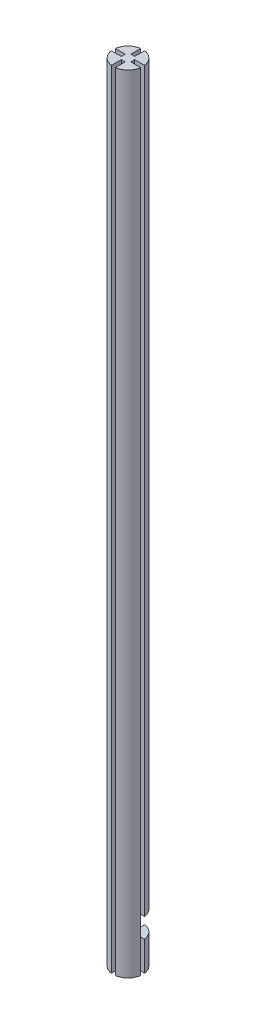
SolidWorks part; units mm, degrees
ref_plane "Front Plane" through (0, 0, 0) normal (0, 0, 1) x (1, 0, 0)
ref_plane "Top Plane" through (0, 0, 0) normal (0, 1, 0) x (1, 0, 0)
ref_plane "Right Plane" through (0, 0, 0) normal (1, 0, 0) x (0, 0, -1)
sketch "Sketch1" plane through (0, 0, 0) normal (0, 1, 0) x (1, 0, 0)
  line L5 (0, 194.153) -> (0, -244.4898) construction
  line L18 (-10, 74.3303) -> (-10, 24.3303)
  line L19 (-10, 24.3303) -> (10, 24.3303)
  line L20 (10, 74.3303) -> (10, 24.3303)
  line L21 (-29.2048, 0) -> (25.2155, 0) construction
  line L22 (74.3303, -10) -> (24.3303, -10)
  line L23 (74.3303, 10) -> (24.3303, 10)
  line L24 (24.3303, 10) -> (24.3303, -10)
  line L25 (-10, -74.3303) -> (-10, -24.3303)
  line L26 (10, -74.3303) -> (10, -24.3303)
  line L27 (10, -24.3303) -> (-10, -24.3303)
  line L28 (-74.3303, 10) -> (-24.3303, 10)
  line L29 (-74.3303, -10) -> (-24.3303, -10)
  line L30 (-24.3303, -10) -> (-24.3303, 10)
  arc A2 (-10, 74.3303) -> (-74.3303, 10) centre (0, 0) ccw
  arc A3 (-74.3303, -10) -> (-10, -74.3303) centre (0, 0) ccw
  arc A4 (10, -74.3303) -> (74.3303, -10) centre (0, 0) ccw
  arc A5 (74.3303, 10) -> (10, 74.3303) centre (0, 0) ccw
  point P1 (0, 24.3303)
  point P4 (0, 93.7498)
  point P24 (-100, 0)
  point P29 (0, 0)
  point P30 (0, 0)
  dimension "D1" = 150
  dimension "D2" = 20
  dimension "D3" = 50
  dimension "D4" = 4
extrude "Boss-Extrude2" add sketch "Sketch1" along normal blind 4000 contours A2 L28 L30 L29 A3 L25 L27 L26 A4 L22 L24 L23 A5 L20 L19 L18
sketch "Sketch2" plane through (0, 0, 0) normal (0, 1, 0) x (1, 0, 0)
  line L0 (0, 74.3303) -> (0, 0)
  line L1 (74.3303, 74.3303) -> (74.3303, 0)
  line L2 (74.3303, 74.3303) -> (0, 74.3303)
  line L3 (74.3303, 0) -> (0, 0)
extrude "Cut-Extrude1" cut sketch "Sketch2" along normal mid plane 100 from offset 200
